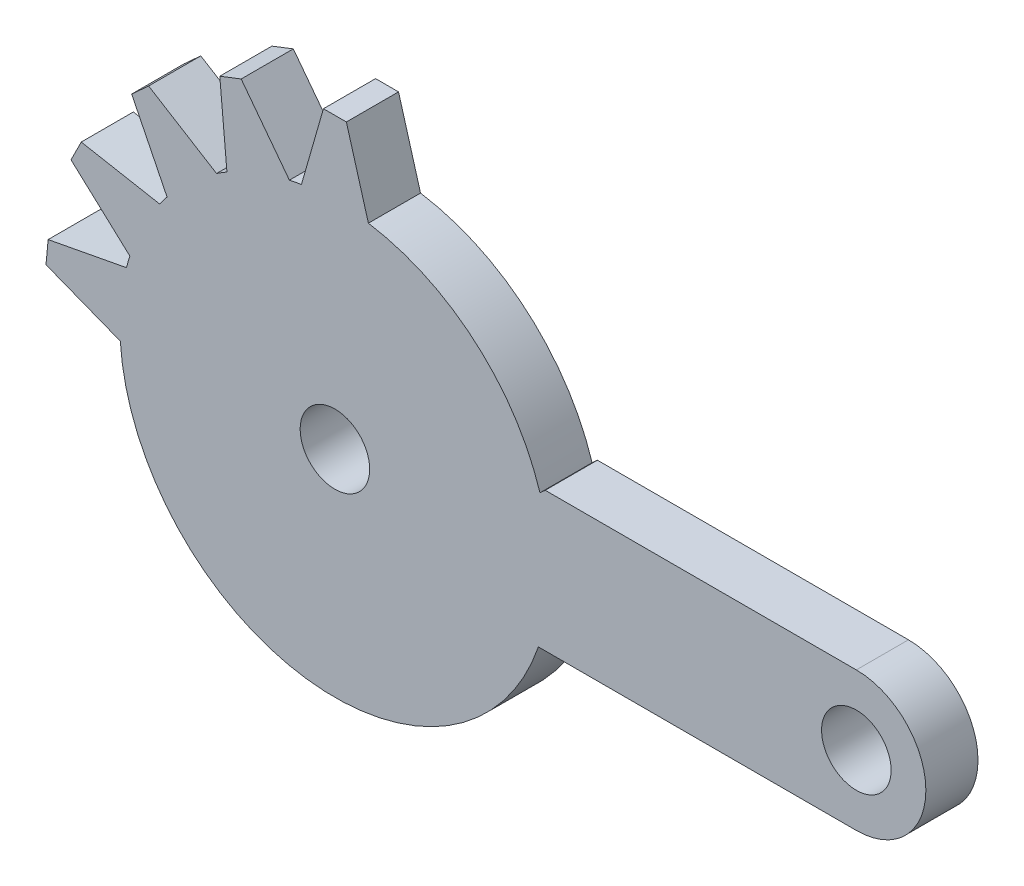
SolidWorks part; units mm, degrees
ref_plane "正面" through (0, 0, 0) normal (0, 0, 1) x (1, 0, 0)
ref_plane "平面" through (0, 0, 0) normal (0, 1, 0) x (1, 0, 0)
ref_plane "右側面" through (0, 0, 0) normal (1, 0, 0) x (0, 0, -1)
sketch "ｽｹｯﾁ1" plane through (0, 0, 0) normal (0, 0, 1) x (1, 0, 0)
  line L2 (-0.6599, 16.6318) -> (-1.9267, 12.2209)
  line L4 (30, -4) -> (11.7074, -4)
  line L6 (-0.6599, 16.6318) -> (0.6599, 16.6318)
  line L7 (0.6599, 16.6318) -> (1.9267, 12.2209)
  line L8 (5.3927, 15.747) -> (6.6234, 15.2703)
  line L9 (6.6234, 15.2703) -> (6.2113, 10.6996)
  line L10 (5.3927, 15.747) -> (2.6181, 12.0916)
  line L11 (10.7171, 12.7356) -> (11.6924, 11.8464)
  line L12 (11.6924, 11.8464) -> (9.657, 7.7333)
  line L13 (10.7171, 12.7356) -> (6.8093, 10.3293)
  line L14 (14.594, 8.0041) -> (15.1823, 6.8227)
  line L15 (15.1823, 6.8227) -> (11.7985, 3.7226)
  line L16 (14.594, 8.0041) -> (10.0809, 7.172)
  line L17 (16.4999, 2.1917) -> (16.6217, 0.8775)
  line L18 (16.6217, 0.8775) -> (12.3465, -0.7909)
  line L19 (16.4999, 2.1917) -> (11.991, 3.0461)
  line L20 (16.1774, -3.9168) -> (15.8162, -5.1862)
  line L21 (15.8162, -5.1862) -> (11.2271, -5.1975)
  line L22 (16.1774, -3.9168) -> (12.2816, -1.4913)
  line L23 (13.6701, -9.4962) -> (12.8747, -10.5495)
  line L24 (12.8747, -10.5495) -> (8.5914, -8.9023)
  line L25 (13.6701, -9.4962) -> (10.9136, -5.8272)
  line L26 (9.3166, -13.7932) -> (8.1944, -14.488)
  line L27 (8.1944, -14.488) -> (4.7954, -11.4047)
  line L28 (9.3166, -13.7932) -> (8.0716, -9.3761)
  line L29 (3.7048, -16.2273) -> (2.4074, -16.4698)
  line L30 (2.4074, -16.4698) -> (0.3517, -12.3668)
  line L31 (3.7048, -16.2273) -> (4.1395, -11.6588)
  line L32 (-2.4074, -16.4698) -> (-3.7048, -16.2273)
  line L33 (-3.7048, -16.2273) -> (-4.1395, -11.6588)
  line L34 (-2.4074, -16.4698) -> (-0.3517, -12.3668)
  line L35 (-8.1944, -14.488) -> (-9.3166, -13.7932)
  line L36 (-9.3166, -13.7932) -> (-8.0716, -9.3761)
  line L37 (-8.1944, -14.488) -> (-4.7954, -11.4047)
  line L38 (-12.8747, -10.5495) -> (-13.6701, -9.4962)
  line L39 (-13.6701, -9.4962) -> (-10.9136, -5.8272)
  line L40 (-12.8747, -10.5495) -> (-8.5914, -8.9023)
  line L41 (-15.8162, -5.1862) -> (-16.1774, -3.9168)
  line L42 (-16.1774, -3.9168) -> (-12.2816, -1.4913)
  line L43 (-15.8162, -5.1862) -> (-11.2271, -5.1975)
  line L44 (-16.6217, 0.8775) -> (-16.4999, 2.1917)
  line L45 (-16.4999, 2.1917) -> (-11.991, 3.0461)
  line L46 (-16.6217, 0.8775) -> (-12.3465, -0.7909)
  line L47 (-15.1823, 6.8227) -> (-14.594, 8.0041)
  line L48 (-14.594, 8.0041) -> (-10.0809, 7.172)
  line L49 (-15.1823, 6.8227) -> (-11.7985, 3.7226)
  line L50 (-11.6924, 11.8464) -> (-10.7171, 12.7356)
  line L51 (-10.7171, 12.7356) -> (-6.8093, 10.3293)
  line L52 (-11.6924, 11.8464) -> (-9.657, 7.7333)
  line L53 (-6.6234, 15.2703) -> (-5.3927, 15.747)
  line L54 (-5.3927, 15.747) -> (-2.6181, 12.0916)
  line L55 (-6.6234, 15.2703) -> (-6.2113, 10.6996)
  line L66 (12.1012, 4) -> (30, 4)
  circle A1 centre (0, 0) radius 12.3718
  circle A2 centre (30, 0) radius 2
  circle A3 centre (30, 0) radius 4
  circle A8 centre (0, 0) radius 2
  point P19 (0, 16.6318)
  point P27 (6.0081, 15.5086)
  point P32 (11.2047, 12.291)
  point P37 (14.8881, 7.4134)
  point P42 (16.5608, 1.5346)
  point P47 (15.9968, -4.5515)
  point P52 (13.2724, -10.0229)
  point P57 (8.7555, -14.1406)
  point P62 (3.0561, -16.3486)
  point P67 (-3.0561, -16.3486)
  point P72 (-8.7555, -14.1406)
  point P77 (-13.2724, -10.0229)
  point P82 (-15.9968, -4.5515)
  point P87 (-16.5608, 1.5346)
  point P92 (-14.8881, 7.4134)
  point P97 (-11.2047, 12.291)
  point P102 (-6.0081, 15.5086)
  point P103 (0, 0)
  dimension "D1" = 17
extrude "ﾎﾞｽ - 押し出し2" add sketch "ｽｹｯﾁ1" along normal blind 3 contours A1 L45 L44 L46 | A1 L48 L47 L49 | A1 L51 L50 L52 | A1 L54 L53 L55 | A1 L7 L6 L2 | A3 L66 L15 A1 L19 L17 L18 L22 L20 L4 | A1 L18 L17 L19 | A1 A8 | A1 L4 L20 L22 | A3 A2
sketch "ｽｹｯﾁ2" plane through (0, 0, 0) normal (0, 0, -1) x (-1, 0, 0)
  circle A0 centre (0, 0) radius 2
  circle A1 centre (0, 0) radius 3.4721
extrude "ﾎﾞｽ - 押し出し5" add sketch "ｽｹｯﾁ2" along normal blind 4.5
